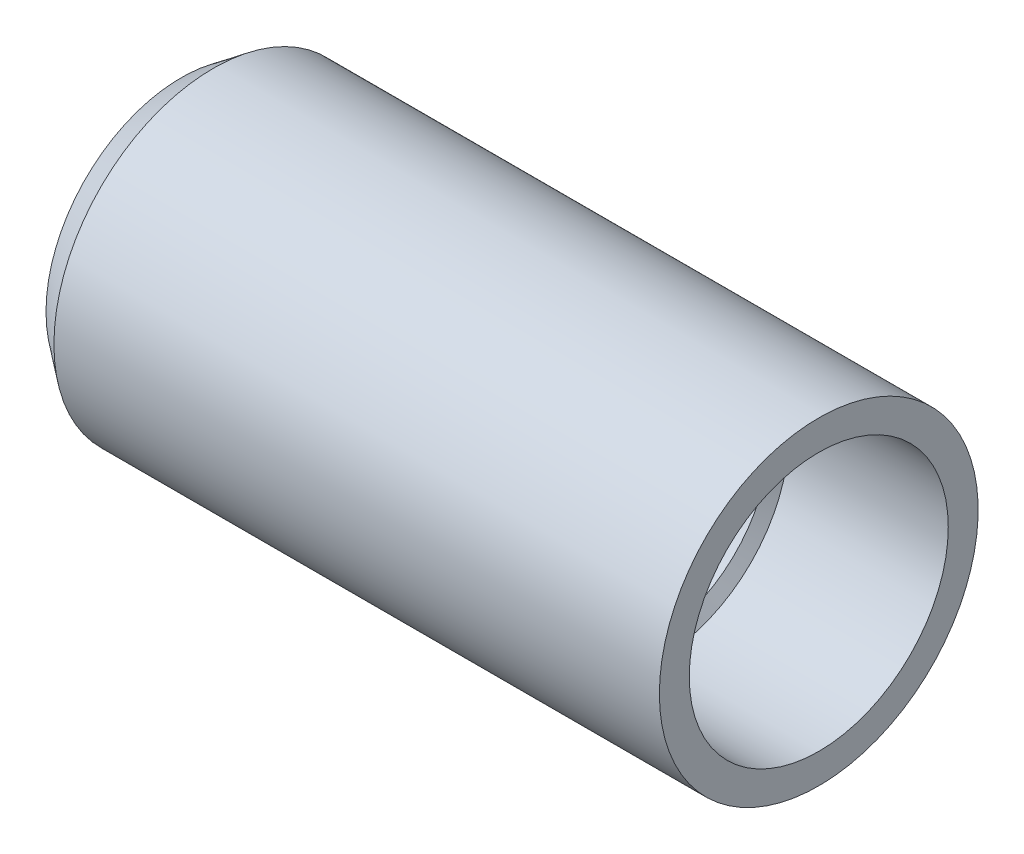
SolidWorks part; units mm, degrees
ref_plane "Front Plane" through (0, 0, 0) normal (0, 0, 1) x (1, 0, 0)
ref_plane "Top Plane" through (0, 0, 0) normal (0, 1, 0) x (1, 0, 0)
ref_plane "Right Plane" through (0, 0, 0) normal (1, 0, 0) x (0, 0, -1)
sketch "Sketch2" plane through (0, 0, 0) normal (0, 0, 1) x (1, 0, 0)
  line L0 (0, 0) -> (49.9611, 0) construction
  line L1 (0, 10.7717) -> (2.559, 12.7)
  line L2 (2.559, 12.7) -> (50.8, 12.7)
  line L3 (50.8, 12.7) -> (50.8, 9.3536)
  line L4 (50.8, 9.3536) -> (25.4, 9.3535)
  line L5 (25.4, 9.3535) -> (25.4, 5.5562)
  line L6 (25.4, 5.5562) -> (0, 5.5562)
  line L7 (0, 5.5562) -> (0, 10.7717)
  line L8 (0, 0) -> (0, 14.8956) construction
  dimension "D1" = 37
  dimension "D2" = 18.7071
  dimension "D3" = 11.1125
  dimension "D4" = 25.4
  dimension "D5" = 25.4
  dimension "D6" = 50.8
  dimension "D7" = 5.2154
revolve "Revolve1" add sketch "Sketch2" angle 360 about L0
hole_wizard "7/8-14 Tapped Hole1" positions "Sketch3" profile "Sketch4" tap size "7/8-14" standard "ANSI Inch"
sketch "Sketch3" plane through (50.8, 0, 0) normal (1, 0, 0) x (0, 0, -1)
  point P0 (0, 0)
sketch "Sketch4" plane through (50.8, 0, 0) normal (0, 1, 0) x (0, 0, -1)
  line L0 (0, 0) -> (0, 18.9001)
  line L1 (0, 18.9001) -> (10.3187, 12.7)
  line L2 (10.3187, 12.7) -> (10.3187, 0)
  line L5 (10.3187, 0) -> (0, 0)
  line L10 (0, 18.9001) -> (-10.3187, 12.7) construction
  line L11 (0, -6.35) -> (0, 107.95) construction
  dimension "Tap Drill Dia." = 20.6375
  dimension "Tap Drill Depth" = 12.7
  dimension "Drill Angle" = 118
cosmetic thread "Hole Thread1"
